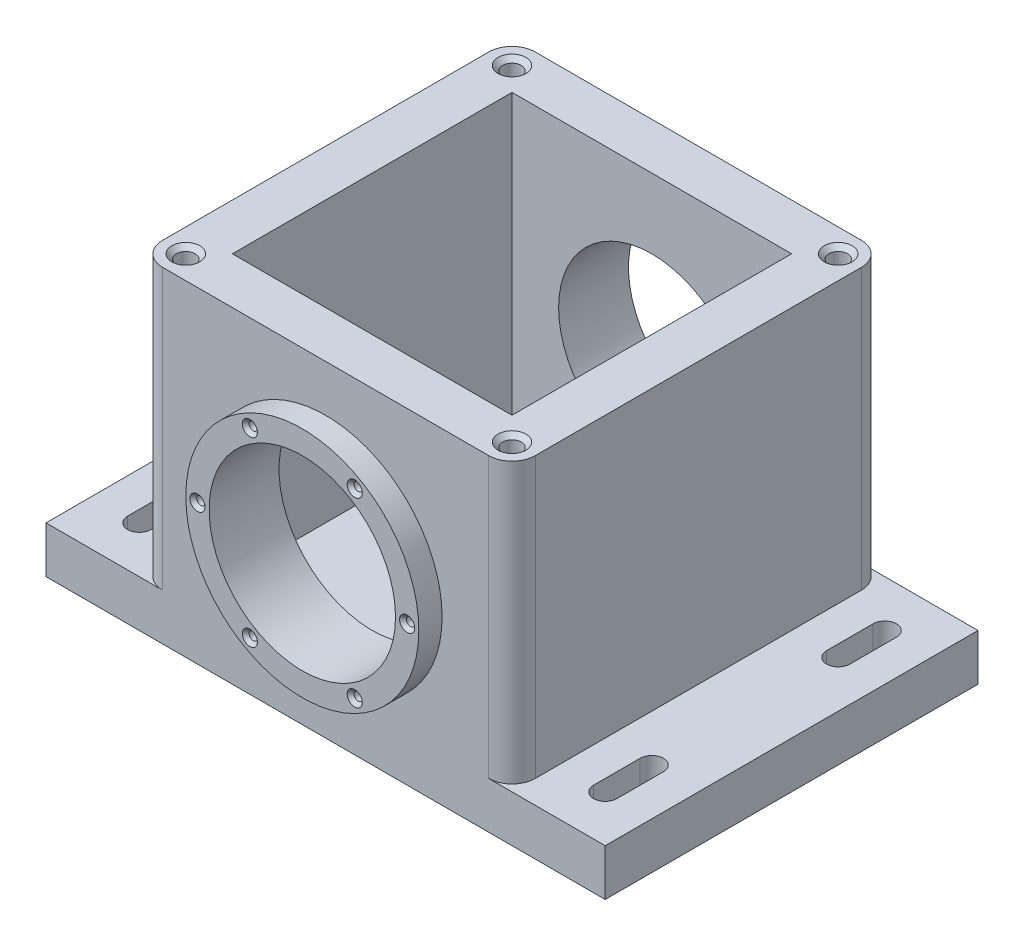
SolidWorks part; units mm, degrees
ref_plane "Front Plane" through (0, 0, 0) normal (0, 0, 1) x (1, 0, 0)
ref_plane "Top Plane" through (0, 0, 0) normal (0, 1, 0) x (1, 0, 0)
ref_plane "Right Plane" through (0, 0, 0) normal (1, 0, 0) x (0, 0, -1)
sketch "Sketch1" plane through (0, 0, 0) normal (0, 1, 0) x (1, 0, 0)
  line L1 (-76.2, -50.8) -> (76.2, -50.8)
  line L2 (-76.2, -50.8) -> (-76.2, 50.8)
  line L3 (-76.2, 50.8) -> (76.2, 50.8)
  line L4 (76.2, -50.8) -> (76.2, 50.8)
  line L5 (-76.2, -50.8) -> (76.2, 50.8) construction
  line L6 (-76.2, 50.8) -> (76.2, -50.8) construction
  point P0 (0, 0)
  dimension "D1" = 101.6
  dimension "D2" = 152.4
extrude "Boss-Extrude1" add sketch "Sketch1" along normal blind 12.7
sketch "Sketch2" plane through (0, 12.7, 0) normal (0, 1, 0) x (1, 0, 0)
  line L0 (76.2, 50.8) -> (-76.2, 50.8) construction
  line L1 (-50.8, -50.8) -> (50.8, -50.8)
  line L2 (-50.8, -50.8) -> (-50.8, 50.8)
  line L3 (-50.8, 50.8) -> (50.8, 50.8)
  line L4 (50.8, -50.8) -> (50.8, 50.8)
  line L5 (-50.8, -50.8) -> (50.8, 50.8) construction
  line L6 (-50.8, 50.8) -> (50.8, -50.8) construction
  point P0 (0, 0)
  dimension "D1" = 101.6
extrude "Boss-Extrude2" add sketch "Sketch2" along normal blind 76.2
sketch "Sketch3" plane through (0, 88.9, 0) normal (0, 1, 0) x (1, 0, 0)
  line L0 (50.8, 50.8) -> (-50.8, 50.8) construction
  line L1 (-38.1, -38.1) -> (38.1, -38.1)
  line L2 (-38.1, -38.1) -> (-38.1, 38.1)
  line L3 (-38.1, 38.1) -> (38.1, 38.1)
  line L4 (38.1, -38.1) -> (38.1, 38.1)
  line L5 (-38.1, -38.1) -> (38.1, 38.1) construction
  line L6 (-38.1, 38.1) -> (38.1, -38.1) construction
  line L7 (50.8, -50.8) -> (50.8, 50.8) construction
  point P0 (0, 0)
  dimension "D1" = 12.7
  dimension "D2" = 12.7
extrude "Cut-Extrude1" cut sketch "Sketch3" against normal blind 76.2
sketch "Sketch4" plane through (0, 0, 50.8) normal (0, 0, 1) x (1, 0, 0)
  line L0 (-50.8, 88.9) -> (50.8, 88.9) construction
  circle A0 centre (0, 44.45) radius 31.75
  dimension "D1" = 63.5
  dimension "D2" = 44.45
extrude "Boss-Extrude3" add sketch "Sketch4" along normal blind 6.35
mirror "Mirror1" about plane through (0, 0, 0) normal (0, 0, 1) of "Boss-Extrude3"
sketch "Sketch5" plane through (0, 0, 57.15) normal (0, 0, 1) x (1, 0, 0)
  circle A0 centre (0, 44.45) radius 25.4
  circle A1 centre (0, 44.45) radius 31.75 construction
  dimension "D1" = 50.8
extrude "Cut-Extrude2" cut sketch "Sketch5" against normal through all
hole_wizard "#4-40 Tapped Hole1" positions "Sketch6" profile "Sketch7" tap size "#4-40" standard "ANSI Inch"
sketch "Sketch6" plane through (0, 0, 57.15) normal (0, 0, 1) x (1, 0, 0)
  line L0 (0, 44.45) -> (0, 73.025) construction
  line L2 (0, 44.45) -> (14.2875, 69.1967) construction
  circle A0 centre (0, 44.45) radius 28.575 construction
  circle A1 centre (0, 44.45) radius 25.4 construction
  point P13 (14.2875, 69.1967)
  dimension "D1" = 57.15
  dimension "D2" = 30
sketch "Sketch7" plane through (14.2875, 69.1967, 57.15) normal (1, 0, 0) x (0, -1, 0)
  line L0 (0, 0) -> (0, 9.5692)
  line L1 (0, 9.5692) -> (1.1303, 8.89)
  line L2 (1.1303, 8.89) -> (1.1303, 0.9271)
  line L3 (1.1303, 0.9271) -> (2.0574, 0)
  line L5 (2.0574, 0) -> (0, 0)
  line L6 (-1.1303, 0.9271) -> (-2.0574, 0) construction
  line L10 (0, 9.5692) -> (-1.1303, 8.89) construction
  line L11 (0, -6.35) -> (0, 107.95) construction
  dimension "Tap Drill Dia." = 2.2606
  dimension "Tap Drill Depth" = 8.89
  dimension "Near C'Sink Dia." = 4.1148
  dimension "Near C'Sink Angle" = 90
  dimension "Drill Angle" = 118
cosmetic thread "Hole Thread1" parameters "D1"=5.588, "D2"=2.8448
pattern_circular "CirPattern1" count 6 over 360 about axis through (0, 44.45, 0) along (0, 0, 1) of "#4-40 Tapped Hole1"
cosmetic thread "Hole Thread2" parameters "D1"=5.588, "D2"=2.8448
cosmetic thread "Hole Thread3" parameters "D1"=5.588, "D2"=2.8448
cosmetic thread "Hole Thread4" parameters "D1"=5.588, "D2"=2.8448
cosmetic thread "Hole Thread5" parameters "D1"=5.588, "D2"=2.8448
cosmetic thread "Hole Thread6" parameters "D1"=5.588, "D2"=2.8448
mirror "Mirror2" about plane through (0, 0, 0) normal (0, 0, 1) of "CirPattern1", "#4-40 Tapped Hole1"
cosmetic thread "Hole Thread7" parameters "D1"=5.588, "D2"=2.8448
cosmetic thread "Hole Thread8" parameters "D1"=5.588, "D2"=2.8448
cosmetic thread "Hole Thread9" parameters "D1"=5.588, "D2"=2.8448
cosmetic thread "Hole Thread10" parameters "D1"=5.588, "D2"=2.8448
cosmetic thread "Hole Thread11" parameters "D1"=5.588, "D2"=2.8448
cosmetic thread "Hole Thread12" parameters "D1"=5.588, "D2"=2.8448
fillet "Fillet1" radius 6.35 4 edges at (-50.8, 50.8, 50.8) (-50.8, 50.8, -50.8) (50.8, 50.8, -50.8) (50.8, 50.8, 50.8)
hole_wizard "1/4-20 Tapped Hole1" positions "Sketch10" profile "Sketch11" tap size "1/4-20" standard "ANSI Inch"
sketch "Sketch10" plane through (0, 88.9, 0) normal (0, 1, 0) x (1, 0, 0)
  point P0 (-44.45, 44.45)
  point P3 (44.45, 44.45)
  point P6 (44.45, -44.45)
  point P9 (-44.45, -44.45)
sketch "Sketch11" plane through (-44.45, 88.9, -44.45) normal (1, 0, 0) x (0, 0, 1)
  line L0 (0, 0) -> (0, 20.5838)
  line L1 (0, 20.5838) -> (2.5527, 19.05)
  line L2 (2.5527, 19.05) -> (2.5527, 1.2573)
  line L3 (2.5527, 1.2573) -> (3.81, 0)
  line L5 (3.81, 0) -> (0, 0)
  line L6 (-2.5527, 1.2573) -> (-3.81, 0) construction
  line L10 (0, 20.5838) -> (-2.5527, 19.05) construction
  line L11 (0, -6.35) -> (0, 107.95) construction
  dimension "Tap Drill Dia." = 5.1054
  dimension "Tap Drill Depth" = 19.05
  dimension "Near C'Sink Dia." = 7.62
  dimension "Near C'Sink Angle" = 90
  dimension "Drill Angle" = 118
cosmetic thread "Hole Thread13" parameters "D1"=12.7, "D2"=6.35
cosmetic thread "Hole Thread14" parameters "D1"=12.7, "D2"=6.35
cosmetic thread "Hole Thread15" parameters "D1"=12.7, "D2"=6.35
cosmetic thread "Hole Thread16" parameters "D1"=12.7, "D2"=6.35
sketch "Sketch12" plane through (0, 12.7, 0) normal (0, 1, 0) x (1, 0, 0)
  line L0 (63.5, -25.4) -> (63.5, -38.1) construction
  line L1 (66.675, -25.4) -> (66.675, -38.1)
  line L2 (60.325, -25.4) -> (60.325, -38.1)
  line L3 (44.45, -50.8) -> (76.2, -50.8) construction
  line L4 (76.2, -50.8) -> (76.2, 50.8) construction
  arc A0 (66.675, -25.4) -> (60.325, -25.4) centre (63.5, -25.4) ccw
  arc A1 (60.325, -38.1) -> (66.675, -38.1) centre (63.5, -38.1) ccw
  point P2 (63.5, -31.75)
  dimension "D1" = 12.7
  dimension "D2" = 12.7
  dimension "D3" = 12.7
  dimension "D4" = 6.35
extrude "Cut-Extrude3" cut sketch "Sketch12" against normal through all
pattern_linear "LPattern1" count 2 spacing 63.5 along (0, 0, -1) of "Cut-Extrude3"
mirror "Mirror3" about plane through (0, 0, 0) normal (1, 0, 0) of "LPattern1", "Cut-Extrude3"
